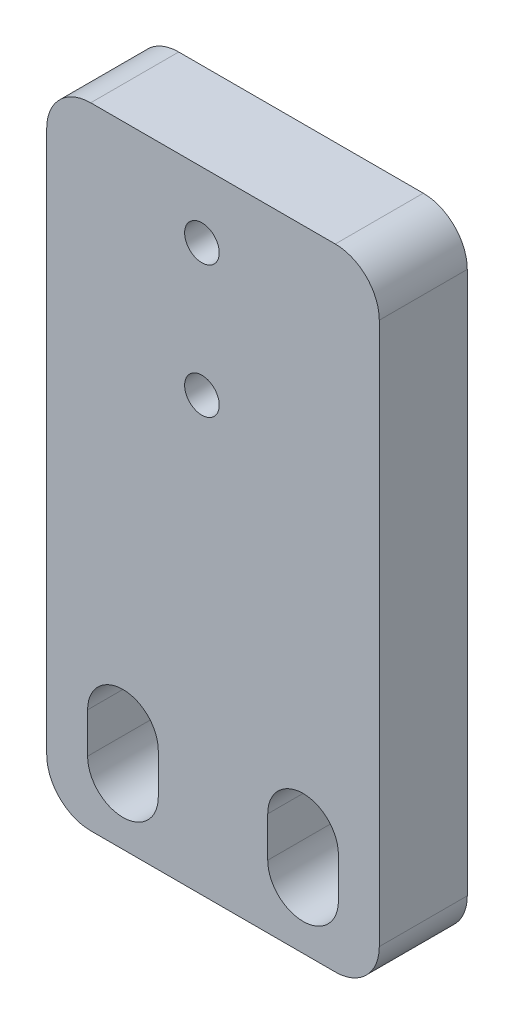
SolidWorks part; units mm, degrees
ref_plane "Front Plane" through (0, 0, 0) normal (0, 0, 1) x (1, 0, 0)
ref_plane "Top Plane" through (0, 0, 0) normal (0, 1, 0) x (1, 0, 0)
ref_plane "Right Plane" through (0, 0, 0) normal (1, 0, 0) x (0, 0, -1)
sketch "Sketch1" plane through (0, 0, 0) normal (0, 0, 1) x (1, 0, 0)
  line L11 (200.7506, 258.9789) -> (200.7506, 219.8289)
  line L12 (203.7006, 221.2039) -> (203.7006, 224.1039)
  line L13 (208.8006, 224.1039) -> (208.8006, 221.2039)
  line L14 (216.7006, 224.1039) -> (216.7006, 221.2039)
  line L23 (221.8006, 221.2039) -> (221.8006, 224.1039)
  line L25 (224.7506, 219.8289) -> (224.7506, 258.9789)
  line L48 (203.9256, 216.6539) -> (221.5756, 216.6539)
  line L66 (221.5756, 262.1539) -> (203.9256, 262.1539)
  arc A42 (200.7506, 219.8289) -> (203.9256, 216.6539) centre (203.9256, 219.8289) ccw
  arc A43 (221.5756, 216.6539) -> (224.7506, 219.8289) centre (221.5756, 219.8289) ccw
  arc A52 (216.7006, 221.2039) -> (221.8006, 221.2039) centre (219.2506, 221.2039) ccw
  arc A53 (221.8006, 224.1039) -> (216.7006, 224.1039) centre (219.2506, 224.1039) ccw
  arc A54 (208.8006, 224.1039) -> (203.7006, 224.1039) centre (206.2506, 224.1039) ccw
  arc A55 (203.7006, 221.2039) -> (208.8006, 221.2039) centre (206.2506, 221.2039) ccw
  arc A62 (224.7506, 258.9789) -> (221.5756, 262.1539) centre (221.5756, 258.9789) ccw
  arc A63 (203.9256, 262.1539) -> (200.7506, 258.9789) centre (203.9256, 258.9789) ccw
  circle A79 centre (211.9506, 247.8914) radius 1.25
  circle A80 centre (211.9506, 257.4164) radius 1.25
extrude "Boss-Extrude1" add sketch "Sketch1" along normal blind 6.35
